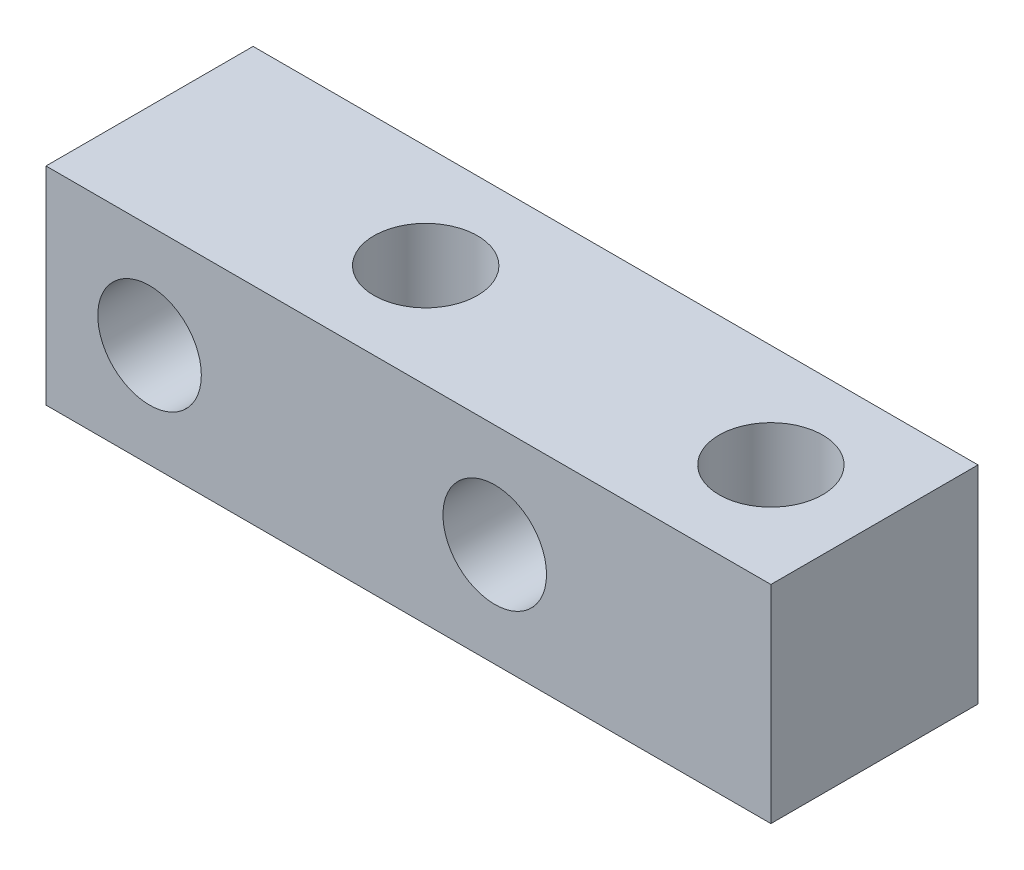
SolidWorks part; units mm, degrees
ref_plane "前视基准面" through (0, 0, 0) normal (0, 0, 1) x (1, 0, 0)
ref_plane "上视基准面" through (0, 0, 0) normal (0, 1, 0) x (1, 0, 0)
ref_plane "右视基准面" through (0, 0, 0) normal (1, 0, 0) x (0, 0, -1)
other "Configuration Table"
sketch "草图1" plane through (0, 0, 0) normal (0, 0, 1) x (1, 0, 0)
  line L1 (-10.5, 3) -> (10.5, 3)
  line L2 (-10.5, 3) -> (-10.5, -3)
  line L3 (-10.5, -3) -> (10.5, -3)
  line L4 (10.5, 3) -> (10.5, -3)
  line L5 (0, -3) -> (0, 3) construction
  line L6 (-10.5, 0) -> (10.5, 0) construction
  point P0 (0, 0)
  dimension "D1" = 6
  dimension "D2" = 21
extrude "凸台-拉伸1" add sketch "草图1" along normal blind 6
sketch "草图2" plane through (0, 0, 6) normal (0, 0, 1) x (1, 0, 0)
  line L0 (-10.5, 0) -> (10.5, 0) construction
  line L1 (-10.5, 3) -> (-10.5, -3) construction
  line L2 (10.5, -3) -> (10.5, 3) construction
  circle A0 centre (-7.5, 0) radius 1.5
  circle A1 centre (2.5, 0) radius 1.5
  dimension "D1" = 3
  dimension "D2" = 3
  dimension "D3" = 3
  dimension "D4" = 10
extrude "切除-拉伸1" cut sketch "草图2" against normal blind 6
sketch "草图3" plane through (0, 3, 0) normal (0, 1, 0) x (1, 0, 0)
  line L0 (-10.5, -3) -> (10.5, -3) construction
  line L1 (-10.5, -6) -> (-10.5, 0) construction
  line L2 (10.5, -6) -> (10.5, 0) construction
  circle A0 centre (7.5, -3) radius 1.5
  circle A1 centre (-2.5, -3) radius 1.5
  dimension "D1" = 3
  dimension "D2" = 3
  dimension "D3" = 3
  dimension "D4" = 10
extrude "切除-拉伸2" cut sketch "草图3" against normal blind 6
